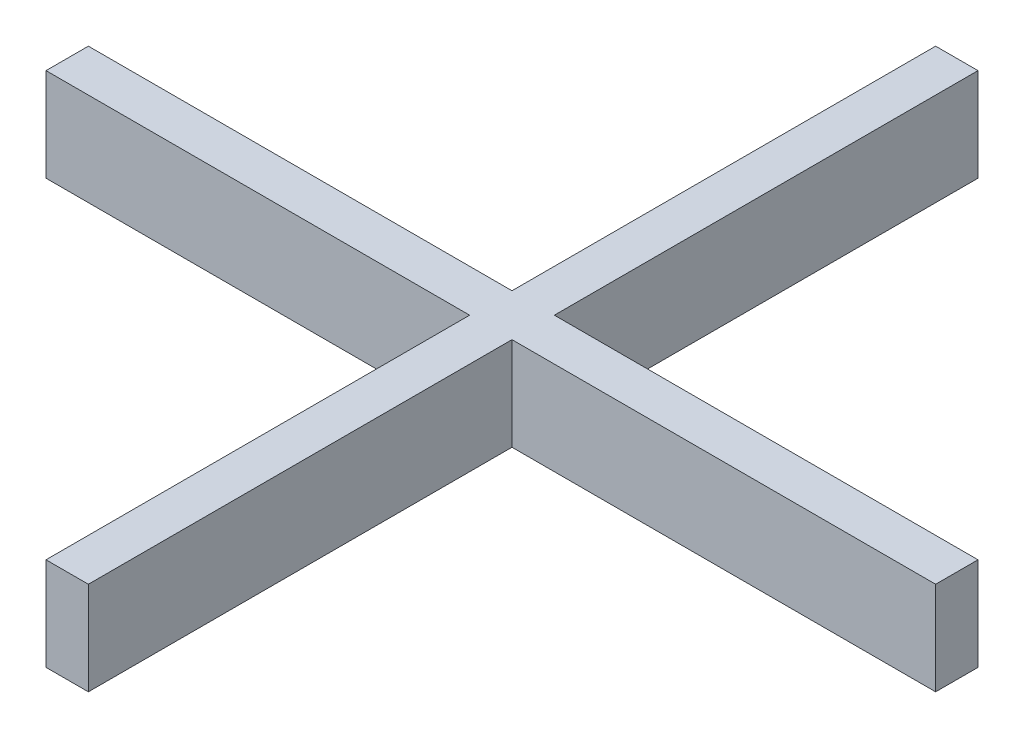
SolidWorks part; units mm, degrees
ref_plane "Front Plane" through (0, 0, 0) normal (0, 0, 1) x (1, 0, 0)
ref_plane "Top Plane" through (0, 0, 0) normal (0, 1, 0) x (1, 0, 0)
ref_plane "Right Plane" through (0, 0, 0) normal (1, 0, 0) x (0, 0, -1)
sketch "Sketch1" plane through (0, 0, 0) normal (0, 1, 0) x (1, 0, 0)
  line L0 (-10.5, 0.5) -> (-0.5, 0.5)
  line L1 (-0.5, 0.5) -> (-0.5, 10.5)
  line L2 (-0.5, 10.5) -> (0.5, 10.5)
  line L3 (0.5, 10.5) -> (0.5, 0.5)
  line L4 (0.5, 0.5) -> (10.5, 0.5)
  line L5 (10.5, 0.5) -> (10.5, -0.5)
  line L6 (10.5, -0.5) -> (0.5, -0.5)
  line L7 (0.5, -0.5) -> (0.5, -10.5)
  line L8 (0.5, -10.5) -> (-0.5, -10.5)
  line L9 (-0.5, -10.5) -> (-0.5, -0.5)
  line L10 (-0.5, -0.5) -> (-10.5, -0.5)
  line L11 (-10.5, -0.5) -> (-10.5, 0.5)
  point P12 (0, -10.5)
  point P14 (-10.5, 0)
  dimension "D1" = 1
  dimension "D2" = 10
extrude "Boss-Extrude1" add sketch "Sketch1" along normal mid plane 2.2
